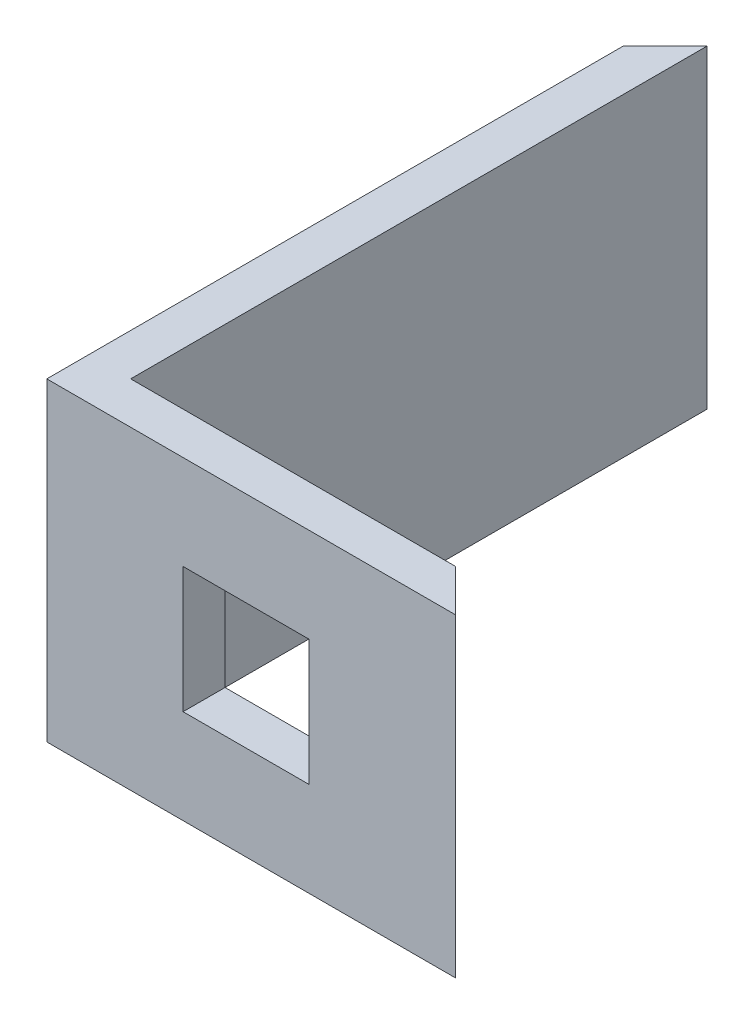
SolidWorks part; units mm, degrees
ref_plane "Front" through (0, 0, 0) normal (0, 0, 1) x (1, 0, 0)
ref_plane "Top" through (0, 0, 0) normal (0, 1, 0) x (1, 0, 0)
ref_plane "Right" through (0, 0, 0) normal (1, 0, 0) x (0, 0, -1)
sketch "Эскиз1" plane through (0, 0, 0) normal (0, 1, 0) x (1, 0, 0)
  line L0 (-2, 25.5) -> (-2, -2)
  line L1 (-2, -2) -> (17.5, -2)
  line L2 (17.5, -2) -> (15.5, 0)
  line L3 (15.5, 0) -> (0, 0)
  line L4 (0, 0) -> (0, 27.5)
  line L5 (0, 27.5) -> (-2, 25.5)
  point P7 (0, 0)
  dimension "D1" = 45
  dimension "D2" = 45
  dimension "D3" = 2
  dimension "D4" = 2
  dimension "D5" = 17.5
  dimension "D6" = 29.5
extrude "Бобышка-Вытянуть1" add sketch "Эскиз1" along normal blind 15
sketch "Эскиз2" plane through (0, 0, 2) normal (0, 0, 1) x (1, 0, 0)
  line L0 (-2, 15) -> (17.5, 15) construction
  line L1 (4.5, 10.5) -> (10.5, 10.5)
  line L2 (4.5, 10.5) -> (4.5, 4.5)
  line L3 (4.5, 4.5) -> (10.5, 4.5)
  line L4 (10.5, 10.5) -> (10.5, 4.5)
  line L5 (-2, 0) -> (17.5, 0) construction
  line L6 (17.5, 15) -> (17.5, 0) construction
  dimension "D1" = 4.5
  dimension "D2" = 4.5
  dimension "D3" = 7
  dimension "D4" = 6
extrude "Вырез-Вытянуть1" cut sketch "Эскиз2" against normal through all
